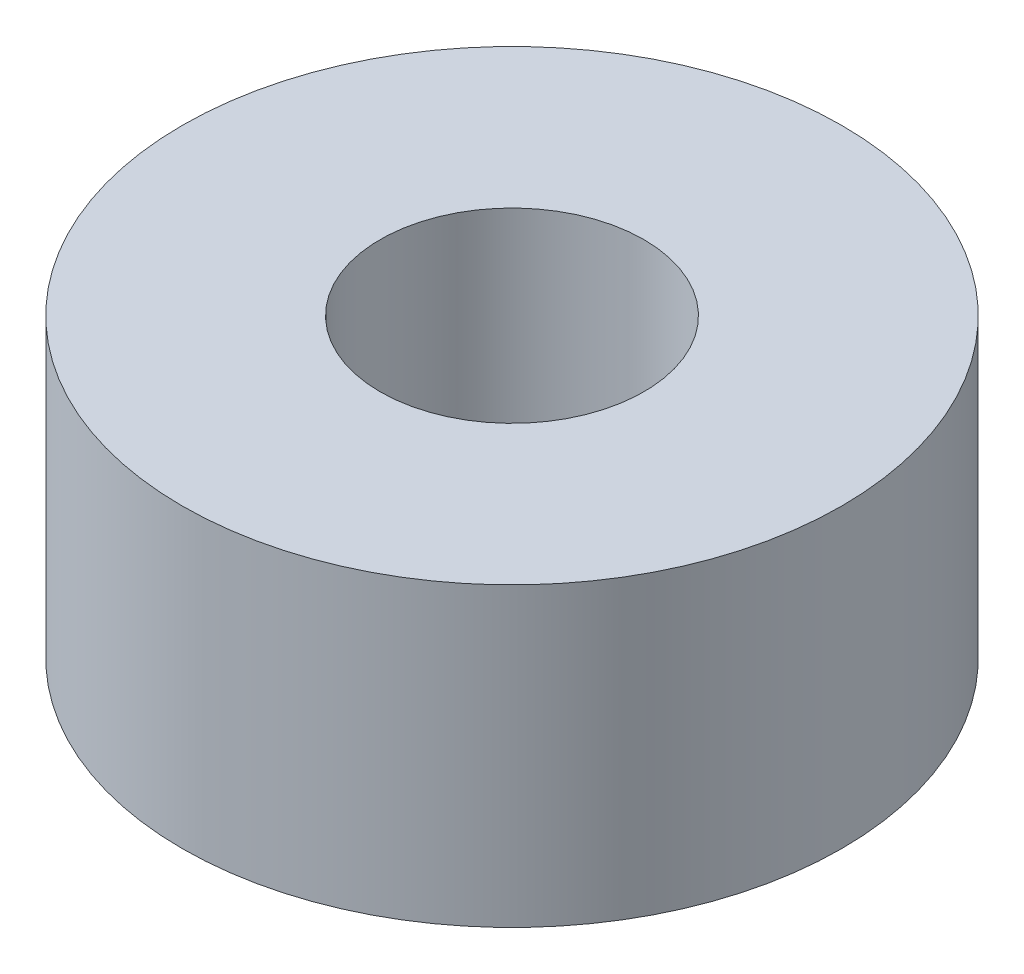
SolidWorks part; units mm, degrees
material "Alloy Steel"
ref_plane "Front Plane" through (0, 0, 0) normal (0, 0, 1) x (1, 0, 0)
ref_plane "Top Plane" through (0, 0, 0) normal (0, 1, 0) x (1, 0, 0)
ref_plane "Right Plane" through (0, 0, 0) normal (1, 0, 0) x (0, 0, -1)
sketch "Sketch1" plane through (0, 0, 0) normal (0, 1, 0) x (1, 0, 0)
  circle A0 centre (0, 0) radius 4
  circle A1 centre (0, 0) radius 10
  dimension "D1" = 8
  dimension "D2" = 20
extrude "Boss-Extrude1" add sketch "Sketch1" along normal blind 9
equation "\"____ GENERATED PART EXPORTS ____\" = 0"
equation "\"SYS_VersionTag\" = 2"
equation "\"HW_CollarBore\" = 8mm"
equation "\"HW_CollarOD\" = 20mm"
equation "\"HW_CollarWidth\" = 9mm"
equation "\"D1@Sketch1\"=\"HW_CollarBore\""
equation "\"D2@Sketch1\"=\"HW_CollarOD\""
equation "\"D1@Boss-Extrude1\"=\"HW_CollarWidth\""
